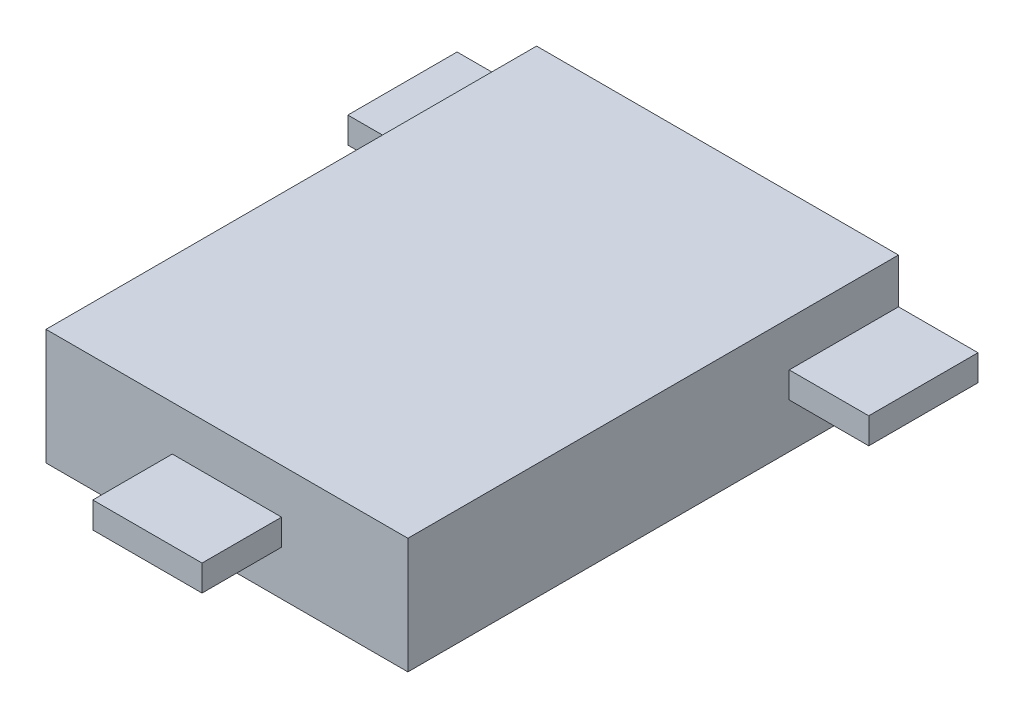
SolidWorks part; units mm, degrees
ref_plane "Front Plane" through (0, 0, 0) normal (0, 0, 1) x (1, 0, 0)
ref_plane "Top Plane" through (0, 0, 0) normal (0, 1, 0) x (1, 0, 0)
ref_plane "Right Plane" through (0, 0, 0) normal (1, 0, 0) x (0, 0, -1)
sketch "Sketch1" plane through (0, 0, 0) normal (0, 1, 0) x (1, 0, 0)
  line L1 (-12.505, -16.9525) -> (12.505, -16.9525)
  line L2 (-12.505, -16.9525) -> (-12.505, 16.9525)
  line L3 (-12.505, 16.9525) -> (12.505, 16.9525)
  line L4 (12.505, -16.9525) -> (12.505, 16.9525)
  line L5 (-12.505, -16.9525) -> (12.505, 16.9525) construction
  line L6 (-12.505, 16.9525) -> (12.505, -16.9525) construction
  point P0 (0, 0)
  dimension "D1" = 33.905
  dimension "D2" = 25.01
extrude "Boss-Extrude1" add sketch "Sketch1" along normal blind 8
sketch "Sketch2" plane through (0, 0, 16.9525) normal (0, 0, 1) x (1, 0, 0)
  line L0 (0, 0) -> (0, 4) construction
  line L2 (-3.775, 3.1) -> (3.775, 3.1)
  line L3 (-3.775, 3.1) -> (-3.775, 4.9)
  line L4 (-3.775, 4.9) -> (3.775, 4.9)
  line L5 (3.775, 3.1) -> (3.775, 4.9)
  line L6 (-3.775, 3.1) -> (3.775, 4.9) construction
  line L7 (-3.775, 4.9) -> (3.775, 3.1) construction
  dimension "D1" = 4
  dimension "D2" = 7.55
  dimension "D3" = 1.8
extrude "Boss-Extrude2" add sketch "Sketch2" along normal blind 5.495
sketch "Sketch3" plane through (-12.505, 0, 0) normal (-1, 0, 0) x (0, 0, 1)
  line L0 (-16.9525, 4) -> (-16.9525, 3.1) construction
  line L1 (-16.9525, 4) -> (-9.4025, 4) construction
  line L3 (-16.9525, 8) -> (-16.9525, 0) construction
  line L4 (-9.4025, 4) -> (-9.4025, 4.9) construction
  line L6 (-16.9525, 3.1) -> (-9.4025, 3.1)
  line L7 (-16.9525, 3.1) -> (-16.9525, 4.9)
  line L8 (-16.9525, 4.9) -> (-9.4025, 4.9)
  line L9 (-9.4025, 3.1) -> (-9.4025, 4.9)
  point P0 (0, 0)
  dimension "D1" = 7.55
  dimension "D2" = 0.9
  dimension "D3" = 0.9
sketch "Sketch4" plane through (-12.505, 0, 0) normal (-1, 0, 0) x (0, 0, 1)
extrude "Boss-Extrude3" add sketch "Sketch3" along normal blind 5.495
mirror "Mirror2" about plane through (0, 0, 0) normal (1, 0, 0) of "Boss-Extrude3"
